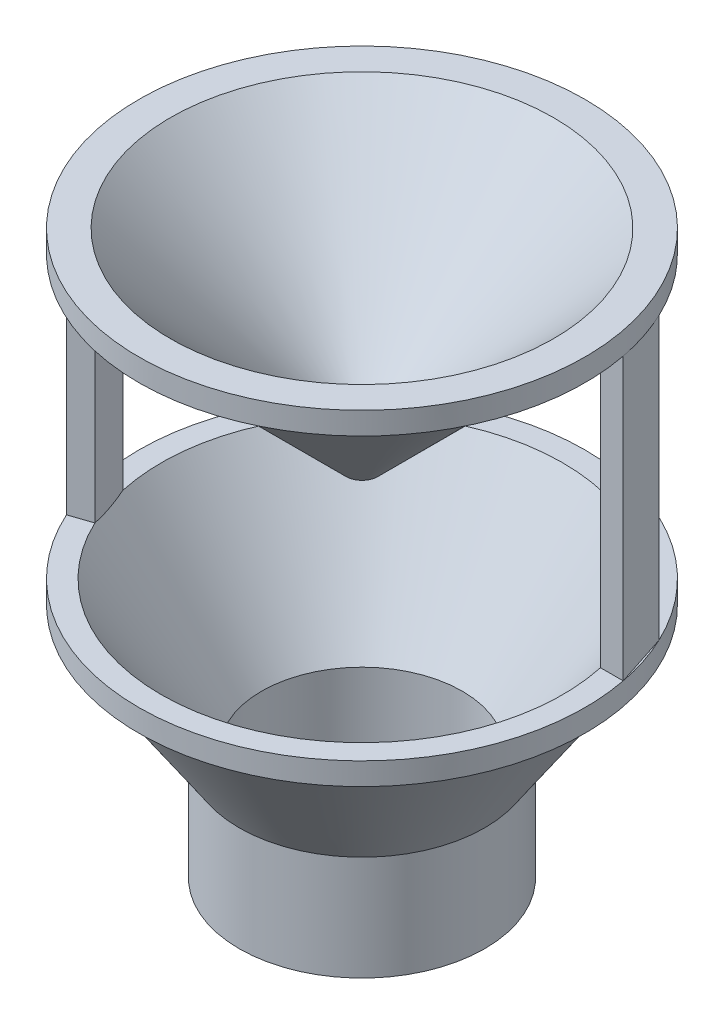
SolidWorks part; units mm, degrees
ref_plane "Front Plane" through (0, 0, 0) normal (0, 0, 1) x (1, 0, 0)
ref_plane "Top Plane" through (0, 0, 0) normal (0, 1, 0) x (1, 0, 0)
ref_plane "Right Plane" through (0, 0, 0) normal (1, 0, 0) x (0, 0, -1)
sketch "Sketch1" plane through (0, 0, 0) normal (0, 0, 1) x (1, 0, 0)
  line L0 (-9, 0) -> (-9, -10)
  line L1 (-9, 0) -> (-18, 13.2288)
  line L2 (-18, 13.2288) -> (-20, 13.2288)
  line L3 (0, 0) -> (0, 17.3566) construction
  point P0 (-9, 0)
  dimension "D1" = 9
  dimension "D2" = 10
  dimension "D3" = 16
  dimension "D4" = 9
  dimension "D5" = 2
revolve "Revolve-Thin3" add sketch "Sketch1" angle 360 about L3
sketch "Sketch5" plane through (0, 0, 0) normal (0, 0, 1) x (1, 0, 0)
  line L0 (0, 0) -> (0, 45.94) construction
  line L1 (18, 13.2288) -> (18, 59.6653) construction
  line L2 (1.4281, 21.8725) -> (18, 38.4444)
  line L3 (18, 38.4444) -> (20, 38.4444)
  dimension "D1" = 2
revolve "Revolve-Thin5" add sketch "Sketch5" angle 360 about L0 wall 2
sketch "Sketch7" plane through (0, 38.4444, 0) normal (0, -1, 0) x (1, 0, 0)
  line L0 (-18.2034, 8.2847) -> (-16.2987, 7.6388)
  line L1 (-16.2987, 7.6388) -> (-17.5833, 3.8507)
  line L2 (-17.5833, 3.8507) -> (-19.488, 4.4965)
  line L3 (-19.488, 4.4965) -> (-18.2034, 8.2847)
  line L4 (-16.941, 5.7447) -> (17.0466, -5.7805) construction
  line L5 (17.0466, -5.7805) -> (16.2316, -7.7805)
  line L6 (16.2316, -7.7805) -> (18.0867, -8.5365)
  line L7 (18.0867, -8.5365) -> (19.6394, -3.7805)
  line L8 (19.6394, -3.7805) -> (17.5985, -3.7805)
  line L9 (17.5985, -3.7805) -> (17.0466, -5.7805)
  circle A0 centre (0, 0) radius 20 construction
  circle A1 centre (0, 0) radius 18 construction
  dimension "D1" = 4
  dimension "D2" = 4
  dimension "D3" = 2
  dimension "D4" = 2
extrude "Boss-Extrude1" add sketch "Sketch7" along normal blind 26
